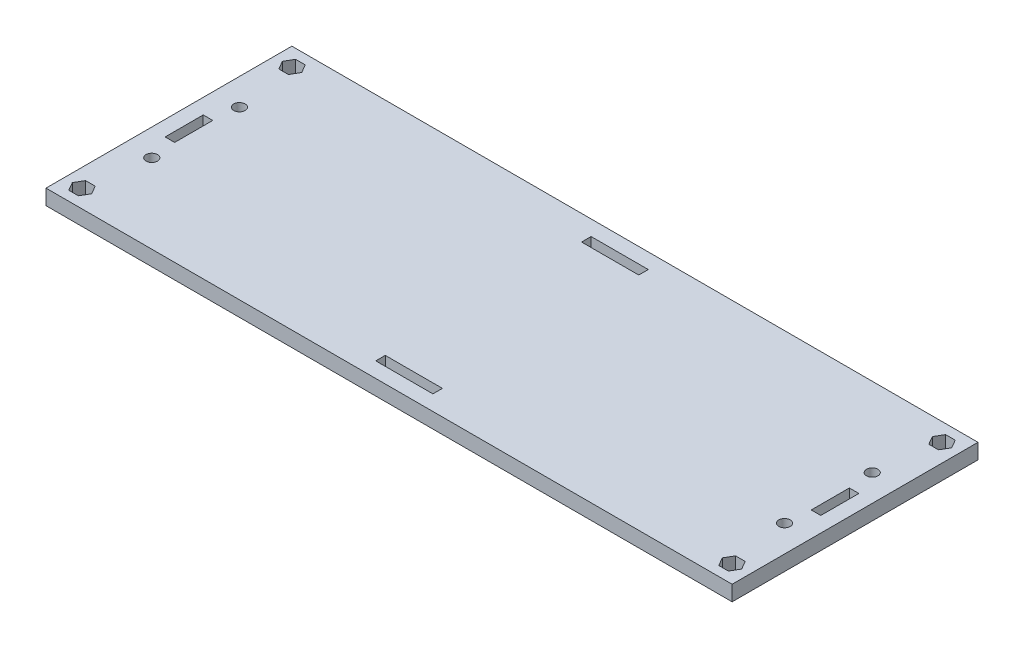
SolidWorks part; units mm, degrees
ref_plane "Alzado" through (0, 0, 0) normal (0, 0, 1) x (1, 0, 0)
ref_plane "Planta" through (0, 0, 0) normal (0, 1, 0) x (1, 0, 0)
ref_plane "Vista lateral" through (0, 0, 0) normal (1, 0, 0) x (0, 0, -1)
sketch "Croquis1" plane through (0, 0, 0) normal (0, 1, 0) x (1, 0, 0)
  line L1 (-90, 32.25) -> (90, 32.25)
  line L2 (-90, 32.25) -> (-90, -32.25)
  line L3 (-90, -32.25) -> (90, -32.25)
  line L4 (90, 32.25) -> (90, -32.25)
  line L5 (-90, 32.25) -> (90, -32.25) construction
  line L6 (-90, -32.25) -> (90, 32.25) construction
  point P0 (0, 0)
  dimension "D1" = 64.5
  dimension "D2" = 180
extrude "Saliente-Extruir1" add sketch "Croquis1" along normal blind 4
sketch "Croquis2" plane through (0, 4, 0) normal (0, 1, 0) x (1, 0, 0)
  line L0 (90, -32.25) -> (90, 32.25) construction
  line L1 (83.5, 5) -> (86, 5)
  line L2 (83.5, 5) -> (83.5, -5)
  line L3 (83.5, -5) -> (86, -5)
  line L4 (86, 5) -> (86, -5)
  line L5 (83.5, 5) -> (86, -5) construction
  line L6 (83.5, -5) -> (86, 5) construction
  point P0 (84.75, 0)
  dimension "D1" = 10
  dimension "D2" = 2.5
  dimension "D3" = 4
extrude "Cortar-Extruir1" cut sketch "Croquis2" against normal up to surface (4 mm away) up to face at (0, 0, 0)
pattern_linear "MatrizL1" count 2 spacing 169.5 along (-1, 0, 0) of "Cortar-Extruir1"
sketch "Croquis3" plane through (0, 0, 0) normal (0, 1, 0) x (1, 0, 0)
  line L0 (90, 32.25) -> (-90, 32.25) construction
  line L1 (-7.5, 28.25) -> (7.5, 28.25)
  line L2 (-7.5, 28.25) -> (-7.5, 25.75)
  line L3 (-7.5, 25.75) -> (7.5, 25.75)
  line L4 (7.5, 28.25) -> (7.5, 25.75)
  line L5 (-7.5, 28.25) -> (7.5, 25.75) construction
  line L6 (-7.5, 25.75) -> (7.5, 28.25) construction
  line L7 (-7.5, -25.75) -> (7.5, -25.75)
  line L8 (-7.5, -28.25) -> (7.5, -28.25)
  line L9 (7.5, -25.75) -> (7.5, -28.25)
  line L10 (-7.5, -25.75) -> (-7.5, -28.25)
  point P0 (0, 27)
  dimension "D1" = 15
  dimension "D2" = 2.5
  dimension "D3" = 4
  dimension "D4" = 2
extrude "Cortar-Extruir2" cut sketch "Croquis3" along normal up to surface (4 mm away) up to face at (-84.75, 4, 0)
sketch "Croquis4" plane through (0, 4, 0) normal (0, 1, 0) x (1, 0, 0)
  line L0 (90, 32.25) -> (-90, 32.25) construction
  line L1 (-82.7193, 27.55) -> (-83.9895, 29.75)
  line L2 (-83.9895, 29.75) -> (-86.5298, 29.75)
  line L3 (-86.5298, 29.75) -> (-87.8, 27.55)
  line L4 (-87.8, 27.55) -> (-86.5298, 25.35)
  line L5 (-86.5298, 25.35) -> (-83.9895, 25.35)
  line L6 (-83.9895, 25.35) -> (-82.7193, 27.55)
  line L7 (-90, 32.25) -> (-90, -32.25) construction
  circle A0 centre (-85.2597, 27.55) radius 2.2 construction
  point P10 (-85.2597, 25.35)
  dimension "D1" = 2.5
  dimension "D2" = 4.4
  dimension "D3" = 2.2
extrude "Cortar-Extruir3" cut sketch "Croquis4" against normal up to surface (4 mm away) up to face at (0, 0, 27)
pattern_linear "MatrizL2" count 2 spacing 170.52 along (1, 0, 0) count 2 spacing 55.1 along (0, 0, 1) of "Cortar-Extruir3"
sketch "Croquis5" plane through (0, 4, 0) normal (0, 1, 0) x (1, 0, 0)
  line L0 (-90, 32.25) -> (-90, -32.25) construction
  line L2 (-90, -32.25) -> (90, -32.25) construction
  line L4 (90, -32.25) -> (90, 32.25) construction
  circle A0 centre (-83, 11.5) radius 1.5
  circle A1 centre (-83, -11.5) radius 1.5
  circle A2 centre (83, -11.5) radius 1.5
  circle A3 centre (83, 11.5) radius 1.5
  dimension "D1" = 3
  dimension "D3" = 3
  dimension "D2" = 7
  dimension "D4" = 23
  dimension "D5" = 20.75
  dimension "D6" = 2
  dimension "D7" = 7
extrude "Cortar-Extruir4" cut sketch "Croquis5" against normal up to surface (4 mm away) up to face at (-85.2597, 0, 27.55)
